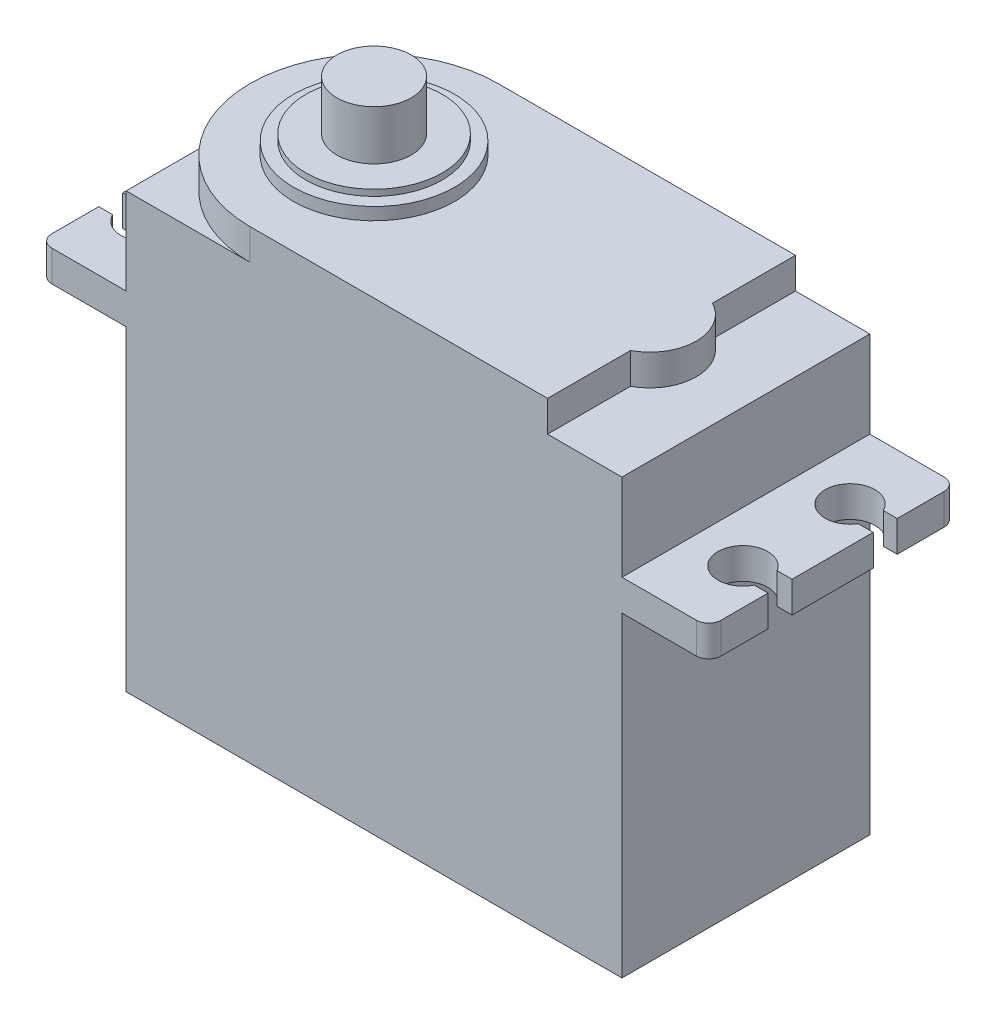
SolidWorks part; units mm, degrees
ref_plane "前视基准面" through (0, 0, 0) normal (0, 0, 1) x (1, 0, 0)
ref_plane "上视基准面" through (0, 0, 0) normal (0, 1, 0) x (1, 0, 0)
ref_plane "右视基准面" through (0, 0, 0) normal (1, 0, 0) x (0, 0, -1)
sketch "草图1" plane through (0, 0, 0) normal (0, 1, 0) x (1, 0, 0)
  line L1 (-20, 10) -> (20, 10)
  line L2 (-20, 10) -> (-20, -10)
  line L3 (-20, -10) -> (20, -10)
  line L4 (20, 10) -> (20, -10)
  line L5 (-20, 10) -> (20, -10) construction
  line L6 (-20, -10) -> (20, 10) construction
  point P0 (0, 0)
  dimension "D1" = 20
  dimension "D2" = 40
extrude "凸台-拉伸1" add sketch "草图1" along normal blind 37
ref_plane "基准面1" through (20, 0, 0) normal (1, 0, 0) x (0, 0, -1)
sketch "草图2" plane through (20, 0, 0) normal (1, 0, 0) x (0, 0, -1)
  line L0 (-17.4829, 30) -> (22.2898, 30) construction
  line L1 (-10, 0) -> (10, 0) construction
  line L2 (-10, 37) -> (-10, 0) construction
  line L3 (-10, 30) -> (10, 30)
  line L4 (-10, 30) -> (-10, 27.5)
  line L5 (-10, 27.5) -> (10, 27.5)
  line L6 (10, 30) -> (10, 27.5)
  line L7 (10, 37) -> (10, 0) construction
  dimension "D1" = 30
  dimension "D2" = 2.5
extrude "凸台-拉伸2" add sketch "草图2" along normal blind 7
fillet "圆角1" radius 1 2 edges at (27, 28.75, -10) (27, 28.75, 10)
sketch "草图3" plane through (0, 0, 0) normal (0, 1, 0) x (1, 0, 0)
  line L0 (17.7171, 0) -> (33.0756, 0) construction
  line L1 (25.882, 5.2097) -> (27, 5.2097)
  line L2 (27, 9) -> (27, -9) construction
  line L3 (27, 5.2097) -> (27, 3.2764)
  line L4 (27, 3.2764) -> (25.793, 3.2764)
  line L5 (27, -3.2764) -> (25.793, -3.2764)
  line L6 (27, -5.2097) -> (27, -3.2764)
  line L7 (25.882, -5.2097) -> (27, -5.2097)
  arc A0 (25.882, 5.2097) -> (25.793, 3.2764) centre (24.0819, 4.3239) ccw
  arc A1 (25.882, -5.2097) -> (25.793, -3.2764) centre (24.0819, -4.3239) cw
extrude "切除-拉伸1" cut sketch "草图3" along normal blind 47
mirror "镜向1" about plane through (0, 0, 0) normal (1, 0, 0) of "切除-拉伸1", "圆角1", "凸台-拉伸2"
ref_plane "基准面2" through (0, 37, 0) normal (0, 1, 0) x (1, 0, 0)
sketch "草图4" plane through (0, 37, 0) normal (0, 1, 0) x (1, 0, 0)
  line L0 (-20, -10) -> (20, -10) construction
  line L1 (20, 10) -> (-20, 10) construction
  line L2 (-20, 10) -> (-20, -10) construction
  line L3 (14, 10) -> (14, 3.3039)
  line L4 (-20, 10) -> (-20, -10) construction
  line L5 (14, 10) -> (-10, 10)
  line L6 (-10, -10) -> (14, -10)
  line L7 (14, -3.3039) -> (14, -10)
  arc A0 (-10, 10) -> (-10, -10) centre (-10, 0) ccw
  arc A1 (14, 3.3039) -> (14, -3.3039) centre (12.2651, 0) cw
  dimension "D1" = 34
extrude "凸台-拉伸3" add sketch "草图4" along normal blind 2.5
sketch "草图6" plane through (0, 37, 0) normal (0, 1, 0) x (1, 0, 0)
  circle A0 centre (-10, 0) radius 6.5
  dimension "D1" = 13
extrude "凸台-拉伸4" add sketch "草图6" along normal blind 3.5
sketch "草图7" plane through (0, 37, 0) normal (0, 1, 0) x (1, 0, 0)
  circle A0 centre (-10, 0) radius 5.5
  dimension "D1" = 11
extrude "凸台-拉伸5" add sketch "草图7" along normal blind 4
sketch "草图8" plane through (0, 37, 0) normal (0, 1, 0) x (1, 0, 0)
  circle A0 centre (-10, 0) radius 3
  dimension "D1" = 6
extrude "凸台-拉伸6" add sketch "草图8" along normal blind 8
chamfer "倒角1" distance 2 angle 45 4 edges at (0, 0, -10) (-20, 0, 0) (0, 0, 10) (20, 0, 0)
